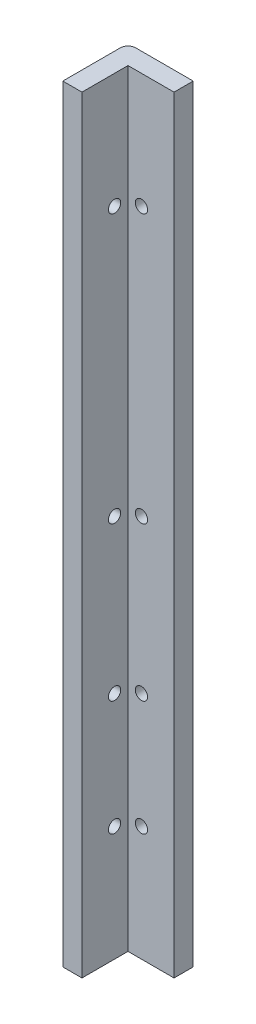
SolidWorks part; units mm, degrees
material "6061-T6 (SS)"
ref_plane "Front Plane" through (0, 0, 0) normal (0, 0, 1) x (1, 0, 0)
ref_plane "Top Plane" through (0, 0, 0) normal (0, 1, 0) x (1, 0, 0)
ref_plane "Right Plane" through (0, 0, 0) normal (1, 0, 0) x (0, 0, -1)
sketch "Sketch2" plane through (0, 0, 0) normal (0, 1, 0) x (1, 0, 0)
  line L0 (0, 0) -> (0, 7.5)
  line L1 (1, 8.5) -> (8.5, 8.5)
  line L2 (8.5, 8.5) -> (8.5, 6)
  line L3 (8.5, 6) -> (2.5, 6)
  line L4 (2.5, 6) -> (2.5, 0)
  line L5 (2.5, 0) -> (0, 0)
  arc A0 (0, 7.5) -> (1, 8.5) centre (1, 7.5) cw
  point P10 (0, 8.5)
  dimension "D3" = 1
  dimension "D1" = 8.5
  dimension "D2" = 2.5
extrude "Boss-Extrude1" add sketch "Sketch2" along normal blind 100
hole_wizard "M2x0.4 Tapped Hole2" positions "Sketch5" profile "Sketch6" tap size "M2x0.4" standard "ANSI Metric" end condition up to next
sketch "Sketch5" plane through (0, 0, -8.5) normal (0, 0, -1) x (-1, 0, 0)
  line L0 (-8.5, 0) -> (-1, 0) construction
  line L2 (-8.5, 100) -> (-8.5, 0) construction
  point P0 (-4.25, 15)
  dimension "D1" = 15
  dimension "D2" = 4.25
sketch "Sketch6" plane through (4.25, 15, -8.5) normal (1, 0, 0) x (0, 1, 0)
  line L0 (0, 0) -> (0, 2.5)
  line L1 (0, 2.5) -> (0.8, 2.5)
  line L2 (0.8, 2.5) -> (0.8, 0.225)
  line L3 (0.8, 0.225) -> (1.025, 0)
  line L5 (1.025, 0) -> (0, 0)
  line L6 (-0.8, 0.225) -> (-1.025, 0) construction
  line L11 (0, -6.35) -> (0, 107.95) construction
  dimension "Thru Tap Drill Dia." = 1.6
  dimension "Thru Tap Drill Depth" = 2.5
  dimension "Near C'Sink Dia." = 2.05
  dimension "Near C'Sink Angle" = 90
cosmetic thread "Hole Thread2" parameters "D2"=2
pattern_linear "LPattern1" count 3 spacing 35 along (0, 1, 0) of "M2x0.4 Tapped Hole2"
cosmetic thread "Hole Thread3" parameters "D2"=2
cosmetic thread "Hole Thread4" parameters "D2"=2
hole_wizard "M2x0.4 Tapped Hole3" positions "Sketch7" profile "Sketch8" tap size "M2x0.4" standard "ANSI Metric" end condition up to next
sketch "Sketch7" plane through (0, 0, 0) normal (-1, 0, 0) x (0, 0, 1)
  line L0 (-7.5, 0) -> (0, 0) construction
  line L1 (0, 100) -> (0, 0) construction
  point P0 (-4.25, 15)
  dimension "D1" = 15
  dimension "D2" = 4.25
sketch "Sketch8" plane through (0, 15, -4.25) normal (0, 1, 0) x (0, 0, 1)
  line L0 (0, 0) -> (0, 2.5)
  line L1 (0, 2.5) -> (0.8, 2.5)
  line L2 (0.8, 2.5) -> (0.8, 0.225)
  line L3 (0.8, 0.225) -> (1.025, 0)
  line L5 (1.025, 0) -> (0, 0)
  line L6 (-0.8, 0.225) -> (-1.025, 0) construction
  line L11 (0, -6.35) -> (0, 107.95) construction
  dimension "Thru Tap Drill Dia." = 1.6
  dimension "Thru Tap Drill Depth" = 2.5
  dimension "Near C'Sink Dia." = 2.05
  dimension "Near C'Sink Angle" = 90
cosmetic thread "Hole Thread5" parameters "D2"=2
pattern_linear "LPattern2" count 3 spacing 35 along (0, 1, 0) of "M2x0.4 Tapped Hole3"
cosmetic thread "Hole Thread6" parameters "D2"=2
cosmetic thread "Hole Thread7" parameters "D2"=2
hole_wizard "M2x0.4 Tapped Hole4" positions "Sketch9" profile "Sketch10" tap size "M2x0.4" standard "ANSI Metric" end condition up to next
sketch "Sketch9" plane through (0, 0, -8.5) normal (0, 0, -1) x (-1, 0, 0)
  line L0 (-8.5, 0) -> (-1, 0) construction
  line L1 (-8.5, 100) -> (-8.5, 0) construction
  point P0 (-4.25, 30)
  dimension "D1" = 30
  dimension "D2" = 4.25
sketch "Sketch10" plane through (4.25, 30, -8.5) normal (1, 0, 0) x (0, 1, 0)
  line L0 (0, 0) -> (0, 2.5)
  line L1 (0, 2.5) -> (0.8, 2.5)
  line L2 (0.8, 2.5) -> (0.8, 0.225)
  line L3 (0.8, 0.225) -> (1.025, 0)
  line L5 (1.025, 0) -> (0, 0)
  line L6 (-0.8, 0.225) -> (-1.025, 0) construction
  line L11 (0, -6.35) -> (0, 107.95) construction
  dimension "Thru Tap Drill Dia." = 1.6
  dimension "Thru Tap Drill Depth" = 2.5
  dimension "Near C'Sink Dia." = 2.05
  dimension "Near C'Sink Angle" = 90
cosmetic thread "Hole Thread8" parameters "D2"=2
hole_wizard "M2x0.4 Tapped Hole5" positions "Sketch11" profile "Sketch12" tap size "M2x0.4" standard "ANSI Metric" end condition up to next
sketch "Sketch11" plane through (0, 0, 0) normal (-1, 0, 0) x (0, 0, 1)
  line L0 (-7.5, 0) -> (0, 0) construction
  line L1 (0, 100) -> (0, 0) construction
  point P0 (-4.25, 30)
  dimension "D1" = 30
  dimension "D2" = 4.25
sketch "Sketch12" plane through (0, 30, -4.25) normal (0, 1, 0) x (0, 0, 1)
  line L0 (0, 0) -> (0, 2.5)
  line L1 (0, 2.5) -> (0.8, 2.5)
  line L2 (0.8, 2.5) -> (0.8, 0.225)
  line L3 (0.8, 0.225) -> (1.025, 0)
  line L5 (1.025, 0) -> (0, 0)
  line L6 (-0.8, 0.225) -> (-1.025, 0) construction
  line L11 (0, -6.35) -> (0, 107.95) construction
  dimension "Thru Tap Drill Dia." = 1.6
  dimension "Thru Tap Drill Depth" = 2.5
  dimension "Near C'Sink Dia." = 2.05
  dimension "Near C'Sink Angle" = 90
cosmetic thread "Hole Thread9" parameters "D2"=2
